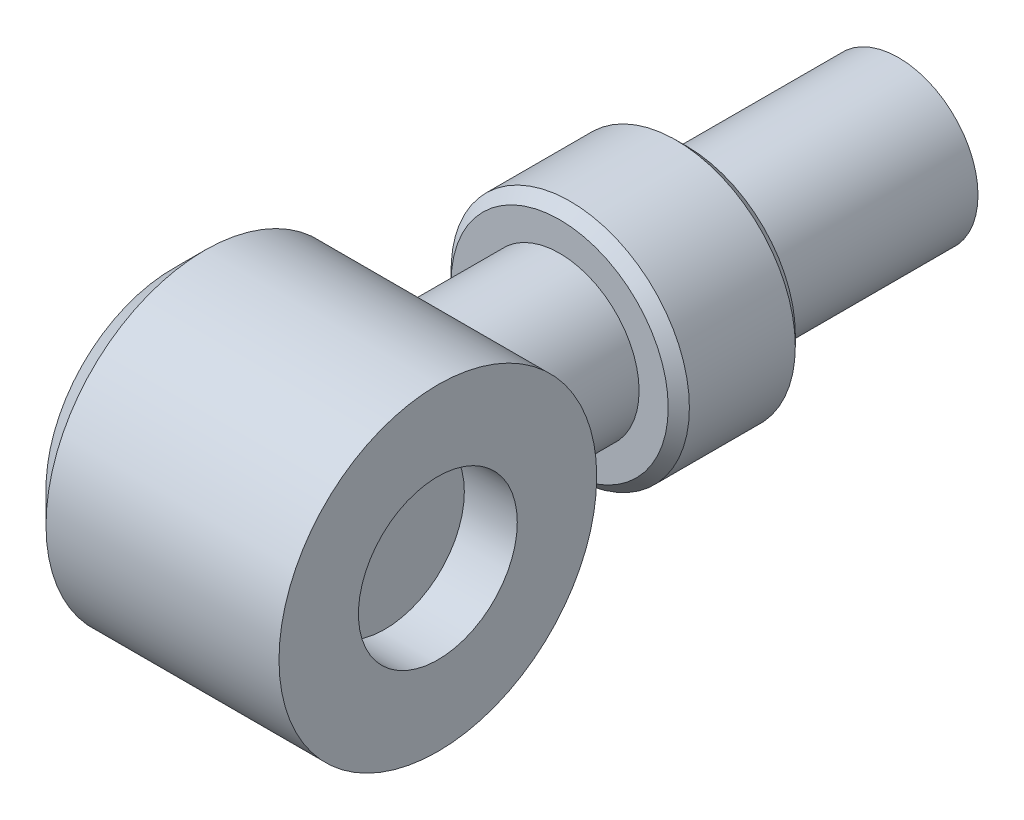
SolidWorks part; units mm, degrees
ref_plane "Front Plane" through (0, 0, 0) normal (0, 0, 1) x (1, 0, 0)
ref_plane "Top Plane" through (0, 0, 0) normal (0, 1, 0) x (1, 0, 0)
ref_plane "Right Plane" through (0, 0, 0) normal (1, 0, 0) x (0, 0, -1)
sketch "Sketch1" plane through (0, 0, 0) normal (0, 0, 1) x (1, 0, 0)
  circle A0 centre (0, 0) radius 22.5
  dimension "D1" = 45
extrude "Boss-Extrude1" add sketch "Sketch1" along normal mid plane 24
sketch "Sketch2" plane through (0, 0, -12) normal (0, 0, -1) x (-1, 0, 0)
  circle A0 centre (0, 0) radius 15
  dimension "D1" = 30
extrude "Boss-Extrude2" add sketch "Sketch2" along normal blind 40
sketch "Sketch3" plane through (0, 0, 0) normal (1, 0, 0) x (0, 0, -1)
  line L0 (-60, 0) -> (0, 0) construction
  circle A0 centre (-60, 0) radius 30
  dimension "D2" = 60
  dimension "D1" = 60
extrude "Boss-Extrude3" add sketch "Sketch3" along normal mid plane 50 separate body
sketch "Sketch4" plane through (0, 0, 12) normal (0, 0, 1) x (1, 0, 0)
  circle A0 centre (0, 0) radius 15
  dimension "D1" = 30
extrude "Boss-Extrude4" add sketch "Sketch4" along normal up to next
chamfer "Chamfer1" distance 6 angle 45 1 edges at (-25, 0, 30)
chamfer "Chamfer2" distance 2 angle 45 2 edges at (22.5, 0, -12) (22.5, 0, 12)
sketch "Sketch5" plane through (25, 0, 0) normal (1, 0, 0) x (0, 0, -1)
  circle A0 centre (-60, 0) radius 15
  dimension "D1" = 30
extrude "Cut-Extrude1" cut sketch "Sketch5" against normal blind 10
